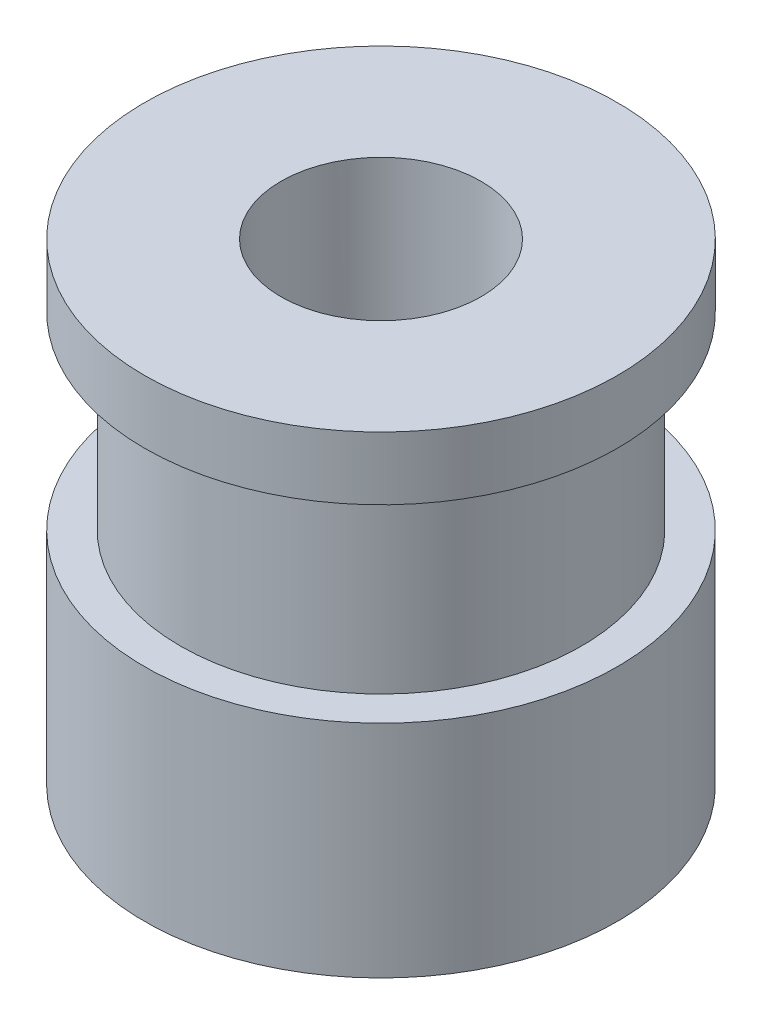
SolidWorks part; units mm, degrees
ref_plane "Front Plane" through (0, 0, 0) normal (0, 0, 1) x (1, 0, 0)
ref_plane "Top Plane" through (0, 0, 0) normal (0, 1, 0) x (1, 0, 0)
ref_plane "Right Plane" through (0, 0, 0) normal (1, 0, 0) x (0, 0, -1)
sketch "Sketch1" plane through (0, 0, 0) normal (0, 1, 0) x (1, 0, 0)
  circle A0 centre (0, 0) radius 6.366
  circle A1 centre (0, 0) radius 3.175
  dimension "D1" = 12.732
  dimension "D2" = 6.35
extrude "Boss-Extrude1" add sketch "Sketch1" along normal blind 10
sketch "Sketch2" plane through (0, 10, 0) normal (0, 1, 0) x (1, 0, 0)
  circle A0 centre (0, 0) radius 7.5
  circle A1 centre (0, 0) radius 3.175
  dimension "D1" = 15
extrude "Boss-Extrude2" add sketch "Sketch2" against normal blind 2
sketch "Sketch3" plane through (0, 0, 0) normal (0, -1, 0) x (1, 0, 0)
  circle A0 centre (0, 0) radius 7.5
  circle A1 centre (0, 0) radius 3.175
  dimension "D1" = 15
  dimension "D2" = 6.35
extrude "Boss-Extrude3" add sketch "Sketch3" against normal blind 2 and the other way blind 5
